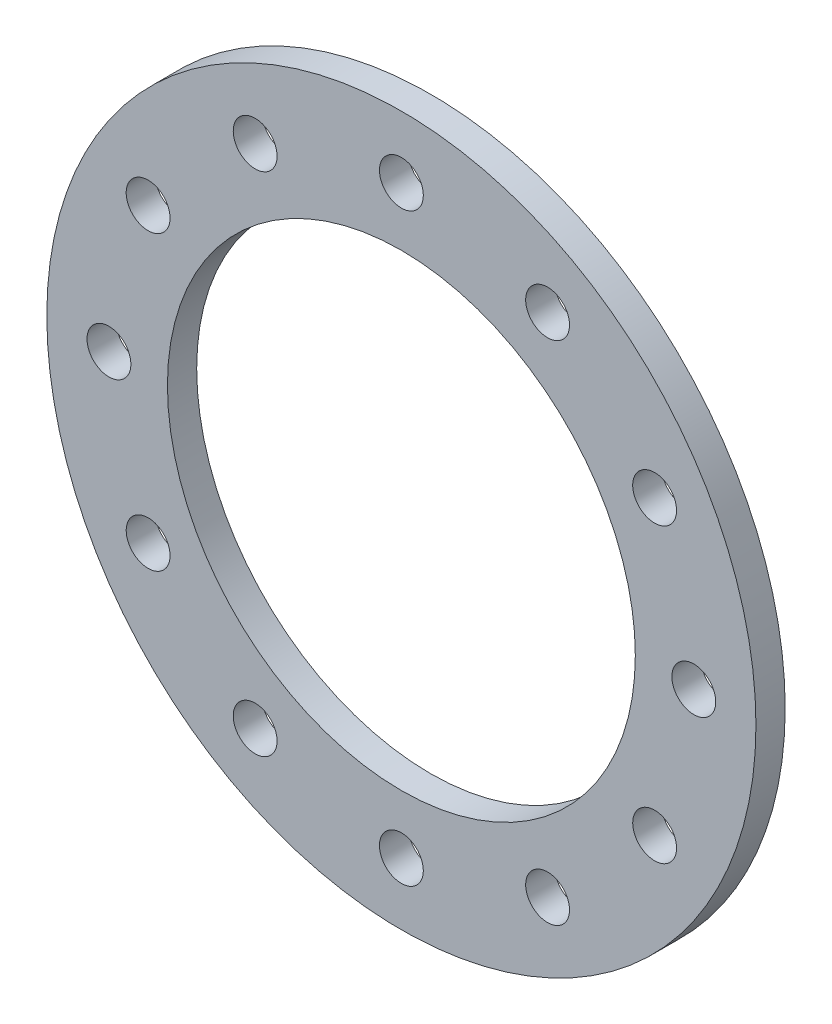
SolidWorks part; units mm, degrees
ref_plane "Спереди" through (0, 0, 0) normal (0, 0, 1) x (1, 0, 0)
ref_plane "Сверху" through (0, 0, 0) normal (0, 1, 0) x (1, 0, 0)
ref_plane "Справа" through (0, 0, 0) normal (1, 0, 0) x (0, 0, -1)
other "Configuration Table"
sketch "Эскиз1" plane through (0, 0, 0) normal (0, 0, 1) x (1, 0, 0)
  circle A0 centre (0, 0) radius 32
  circle A1 centre (0, 0) radius 48.5
  dimension "D1" = 97
  dimension "D2" = 64
extrude "Бобышка-Вытянуть1" add sketch "Эскиз1" along normal blind 4
sketch "Эскиз2" plane through (0, 0, 0) normal (0, 0, -1) x (-1, 0, 0)
  circle A0 centre (0, 40) radius 3
  dimension "D1" = 6
  dimension "D2" = 40
extrude "Вырез-Вытянуть1" cut sketch "Эскиз2" against normal blind 18.6
pattern_circular "Круговой массив1" count 12 over 360 about axis through (0, 0, 0) along (0, 0, 1) of "Вырез-Вытянуть1"
